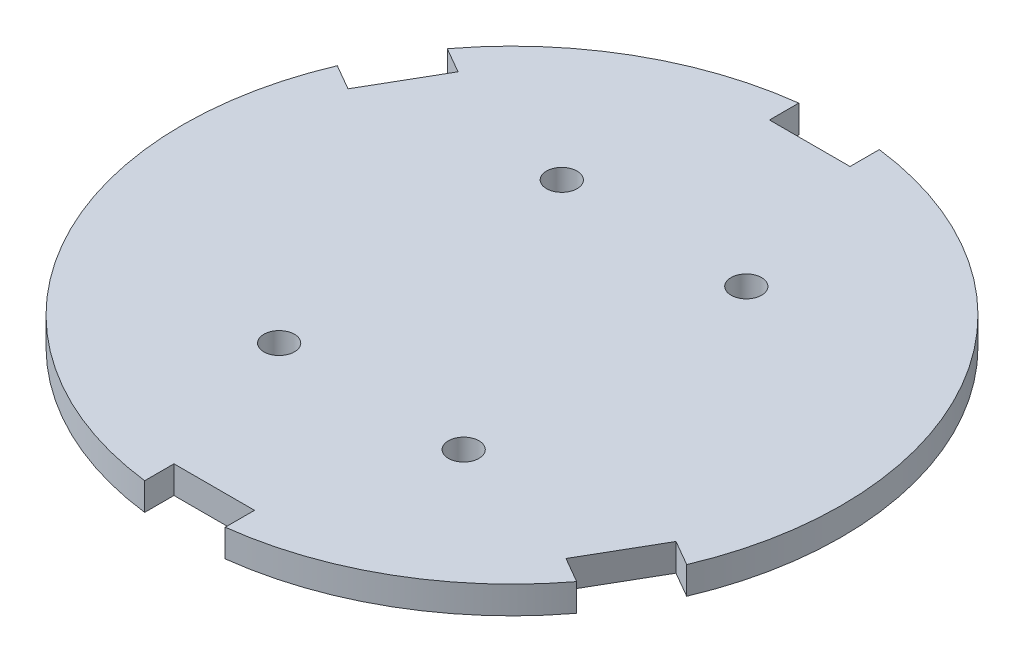
SolidWorks part; units mm, degrees
material "6061-T6 (SS)"
ref_plane "Front Plane" through (0, 0, 0) normal (0, 0, 1) x (1, 0, 0)
ref_plane "Top Plane" through (0, 0, 0) normal (0, 1, 0) x (1, 0, 0)
ref_plane "Right Plane" through (0, 0, 0) normal (1, 0, 0) x (0, 0, -1)
sketch "Sketch1" plane through (0, 0, 0) normal (0, 1, 0) x (1, 0, 0)
  circle A0 centre (0, 0) radius 57.15
  dimension "D1" = 114.3
extrude "Boss-Extrude1" add sketch "Sketch1" along normal blind 4.7625
sketch "Sketch2" plane through (0, 4.7625, 0) normal (0, 1, 0) x (1, 0, 0)
  line L0 (0, 0) -> (0, -55.8813) construction
  line L1 (0, 0) -> (59.2491, 0) construction
  line L2 (-6.985, -51.6415) -> (6.985, -51.6415)
  line L3 (6.985, -51.6415) -> (6.985, -56.7215)
  line L4 (-6.985, -51.6415) -> (-6.985, -56.7215)
  line L5 (-6.985, 51.6415) -> (-6.985, 56.7215)
  line L6 (-6.985, 51.6415) -> (6.985, 51.6415)
  line L7 (6.985, 51.6415) -> (6.985, 56.7215)
  circle A0 centre (0, 0) radius 57.15 construction
  arc A1 (-6.985, -56.7215) -> (6.985, -56.7215) centre (0, 0) ccw
  arc A2 (-6.985, 56.7215) -> (6.985, 56.7215) centre (0, 0) cw
  point P7 (0, -51.6415)
  dimension "D1" = 13.97
  dimension "D2" = 5.08
extrude "Cut-Extrude1" cut sketch "Sketch2" against normal up to next
sketch "Sketch3" plane through (0, 4.7625, 0) normal (0, 1, 0) x (1, 0, 0)
  line L0 (0, 0) -> (49.3026, -28.4649) construction
  line L1 (0, 0) -> (26.5906, 46.0563) construction
  line L2 (0, -55) -> (0, 55) construction
  line L3 (41.2304, -31.87) -> (48.2154, -19.7716)
  line L4 (41.2304, -31.87) -> (45.6298, -34.41)
  line L5 (48.2154, -19.7716) -> (52.6148, -22.3116)
  line L6 (-41.2304, 31.87) -> (-45.6298, 34.41)
  line L7 (-48.2154, 19.7716) -> (-41.2304, 31.87)
  line L8 (-48.2154, 19.7716) -> (-52.6148, 22.3116)
  arc A0 (6.985, -56.7215) -> (6.985, 56.7215) centre (0, 0) ccw construction
  arc A1 (52.6148, -22.3116) -> (45.6298, -34.41) centre (0, 0) cw
  arc A2 (-45.6298, 34.41) -> (-52.6148, 22.3116) centre (0, 0) ccw
  point P7 (44.7229, -25.8208)
  dimension "D1" = 60
  dimension "D2" = 13.97
  dimension "D3" = 5.08
extrude "Cut-Extrude2" cut sketch "Sketch3" against normal up to next
sketch "Sketch5" plane through (0, 4.7625, 0) normal (0, 1, 0) x (1, 0, 0)
  line L0 (0, 0) -> (0, -28.321)
  line L1 (0, 0) -> (0, 28.321)
  circle A0 centre (16.002, 24.638) radius 1.778
  circle A1 centre (-16.002, 24.638) radius 1.778
  circle A2 centre (16.002, -24.384) radius 1.778
  circle A3 centre (-16.002, -24.384) radius 1.778
  point P12 (0, 0)
  point P13 (0, 0)
  point P14 (0, 0)
  point P15 (0, 0)
  point P16 (36.7456, 73.1836)
  point P17 (0, 0)
  point P18 (0, 0)
  dimension "D1" = 3.556
  dimension "D2" = 3.556
  dimension "D3" = 3.556
  dimension "D4" = 3.556
  dimension "D5" = 16.002
  dimension "D6" = 16.002
  dimension "D7" = 24.638
  dimension "D8" = 24.638
  dimension "D9" = 49.022
  dimension "D10" = 16.002
  dimension "D11" = 16.002
  dimension "D12" = 49.022
hole_wizard "#4 (0.209) Diameter Hole1" positions "3DSketch1" profile "Sketch6" hole size "#4" standard "ANSI Inch" end condition up to next
sketch3d "3DSketch1"
  point P0 (16.002, 4.7625, -24.638)
  point P3 (16.002, 4.7625, 24.384)
  point P6 (-16.002, 4.7625, 24.384)
  point P9 (-16.002, 4.7625, -24.638)
sketch "Sketch6" plane through (16.002, 4.7625, -24.638) normal (1, 0, 0) x (0, 0, 1)
  line L0 (0, 0) -> (0, 4.7625)
  line L1 (0, 4.7625) -> (2.6543, 4.7625)
  line L2 (2.6543, 4.7625) -> (2.6543, 0)
  line L5 (2.6543, 0) -> (0, 0)
  line L11 (0, -6.35) -> (0, 107.95) construction
  dimension "Thru Hole Dia." = 5.3086
  dimension "Thru Hole Depth" = 4.7625
equation "\"Bulkhead\"=4.5"
equation "\"D1@Sketch1\"=\"Bulkhead\""
